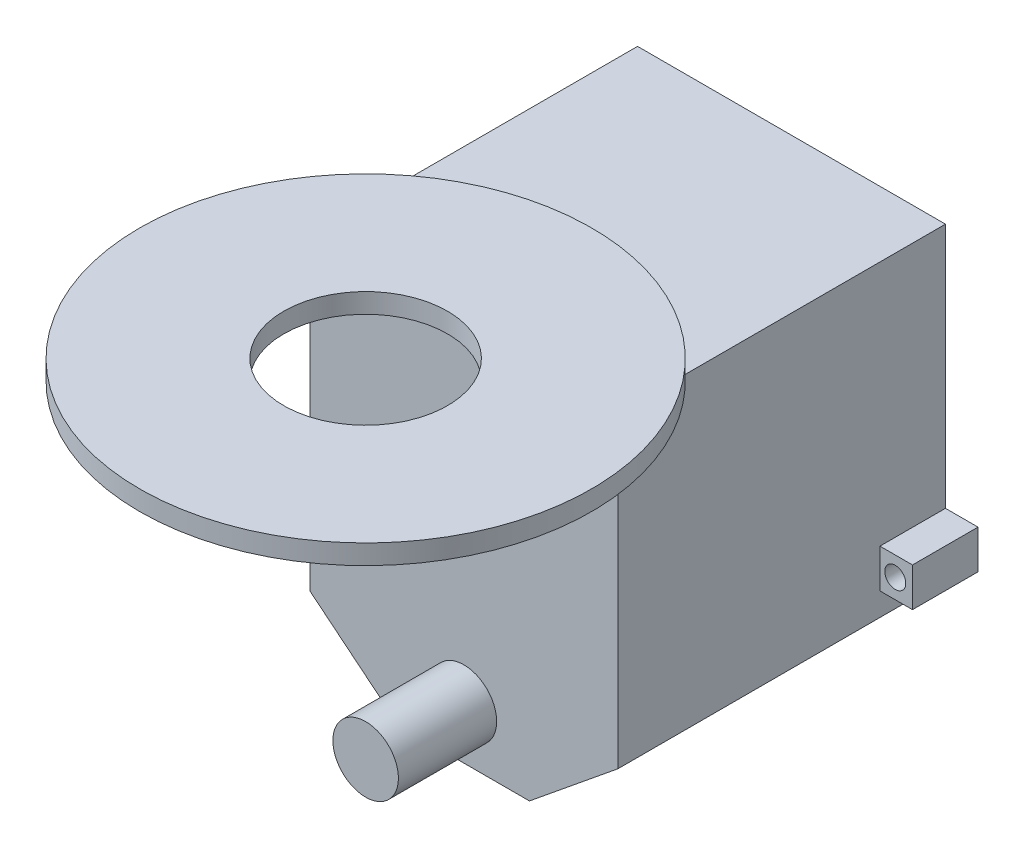
SolidWorks part; units mm, degrees
ref_plane "前视基准面" through (0, 0, 0) normal (0, 0, 1) x (1, 0, 0)
ref_plane "上视基准面" through (0, 0, 0) normal (0, 1, 0) x (1, 0, 0)
ref_plane "右视基准面" through (0, 0, 0) normal (1, 0, 0) x (0, 0, -1)
sketch "草图1" plane through (0, 0, 0) normal (0, 0, 1) x (1, 0, 0)
  line L0 (10, 0) -> (-10, 0)
  line L1 (-10, 0) -> (-23.5, 11)
  line L2 (-23.5, 11) -> (-23.5, 58)
  line L3 (-23.5, 58) -> (23.5, 58)
  line L4 (0, 58) -> (0, -14.397) construction
  line L5 (23.5, 11) -> (23.5, 58)
  line L6 (10, 0) -> (23.5, 11)
  point P11 (0, 0)
  dimension "D1" = 47
  dimension "D2" = 47
  dimension "D3" = 58
  dimension "D4" = 20
extrude "凸台-拉伸1" add sketch "草图1" along normal blind 50
sketch "草图2" plane through (0, 0, 0) normal (0, 0, -1) x (-1, 0, 0)
  line L12 (9.2884, 2) -> (21.5, 11.9502)
  line L13 (21.5, 11.9502) -> (21.5, 56)
  line L14 (21.5, 56) -> (-21.5, 56)
  line L15 (-21.5, 56) -> (-21.5, 11.9502)
  line L16 (-21.5, 11.9502) -> (-9.2884, 2)
  line L17 (-9.2884, 2) -> (9.2884, 2)
  line L18 (9.2884, 2) -> (21.5, 11.9502)
  line L19 (21.5, 11.9502) -> (21.5, 56)
  line L20 (21.5, 56) -> (-21.5, 56)
  line L21 (-21.5, 56) -> (-21.5, 11.9502)
  line L22 (-21.5, 11.9502) -> (-9.2884, 2)
  line L23 (-9.2884, 2) -> (9.2884, 2)
  dimension "D1" = 2
extrude "切除-拉伸1" cut sketch "草图2" against normal offset from surface (48 mm away) 2 up to face at (0, 23, 50)
sketch "草图3" plane through (0, 0, 0) normal (0, 0, -1) x (-1, 0, 0)
  line L0 (-23.5, 20.4346) -> (-28.4664, 20.4346)
  line L1 (-23.5, 11) -> (-23.5, 58) construction
  line L2 (-28.4664, 20.4346) -> (-28.4664, 14.5178)
  line L3 (-28.4664, 14.5178) -> (-23.5, 14.5178)
  line L4 (-23.5, 14.5178) -> (-23.5, 20.4346)
  circle A0 centre (-25.8367, 17.4762) radius 1.6
  dimension "D1" = 3.2
extrude "凸台-拉伸2" add sketch "草图3" against normal blind 10
ref_plane "基准面1" through (0, 0, 0) normal (1, 0, 0) x (0, 0, -1)
mirror "镜向1" about plane through (0, 0, 0) normal (1, 0, 0) of "凸台-拉伸2"
sketch "草图4" plane through (0, 0, 0) normal (0, 0, -1) x (-1, 0, 0)
  line L0 (-1.4133, 0) -> (3.2549, 0)
  line L1 (10, 0) -> (-10, 0) construction
  line L2 (3.2549, 0) -> (3.2549, -4.516)
  line L3 (3.2549, -4.516) -> (-1.4133, -4.516)
  line L4 (-1.4133, -4.516) -> (-1.4133, 0)
  circle A0 centre (1.1613, -2.3265) radius 1.6
  dimension "D1" = 3.2
extrude "凸台-拉伸3" add sketch "草图4" against normal blind 10 separate body contours A0 | L4 L0 L2 L3
sketch "草图5" plane through (0, 0, 50) normal (0, 0, 1) x (1, 0, 0)
  line L0 (0, 58) -> (0, -17.1472) construction
  line L1 (23.5, 58) -> (-23.5, 58) construction
  line L2 (0, -25.85) -> (0, 25.85) construction
  line L3 (-10, 0) -> (10, 0) construction
  circle A0 centre (0, 8) radius 5
  dimension "D1" = 10
  dimension "D2" = 8
extrude "凸台-拉伸4" add sketch "草图5" along normal blind 15
sketch "草图8" plane through (0, 58, 0) normal (0, 1, 0) x (1, 0, 0)
  line L0 (0, -25.85) -> (0, 25.85) construction
  line L1 (0, 0) -> (0, -83.1714) construction
  line L2 (23.5, -50) -> (-23.5, -50) construction
  circle A0 centre (0, -65) radius 34.5
  point P7 (0, -62.3786)
  dimension "D1" = 69
  dimension "D2" = 15
extrude "凸台-拉伸6" add sketch "草图8" along normal blind 3
sketch "草图9" plane through (0, 61, 0) normal (0, 1, 0) x (1, 0, 0)
  circle A0 centre (0, -65) radius 12.5
  dimension "D1" = 25
extrude "切除-拉伸3" cut sketch "草图9" against normal blind 3
